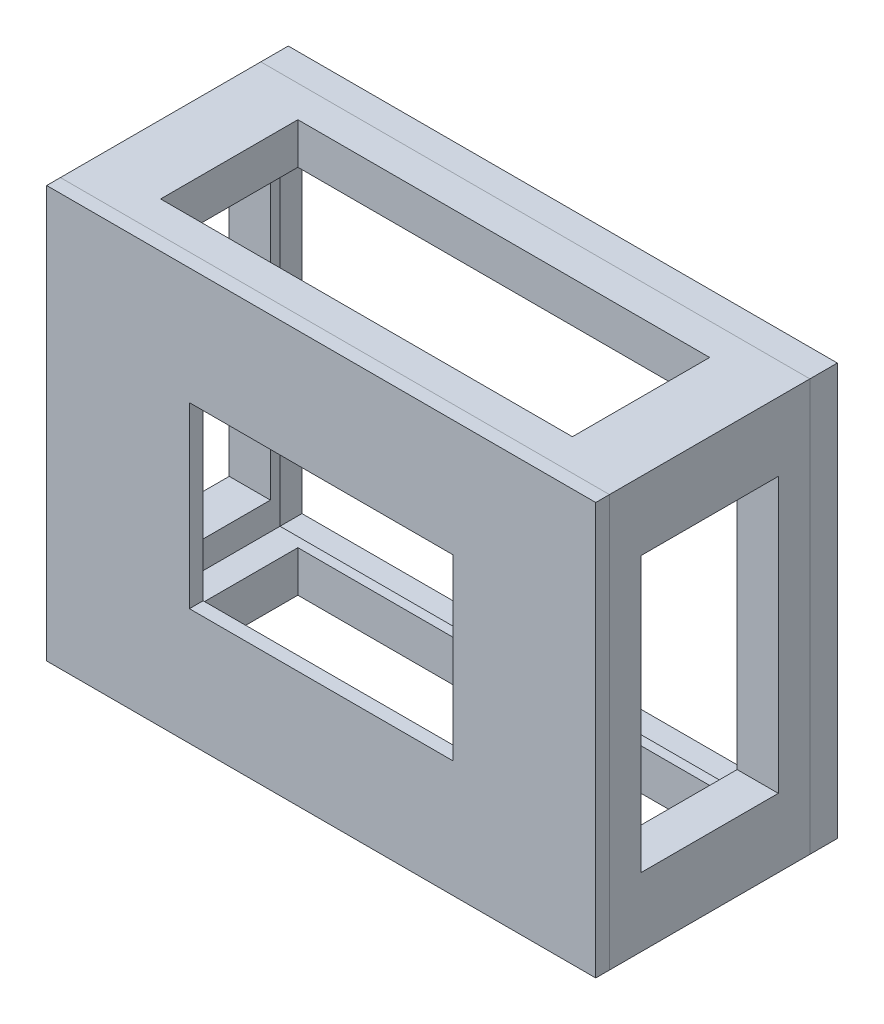
SolidWorks part; units mm, degrees
ref_plane "Front Plane" through (0, 0, 0) normal (1, 0, 0) x (0, 1, 0)
ref_plane "Top Plane" through (0, 0, 0) normal (0, 0, 1) x (0, 1, 0)
ref_plane "Right Plane" through (0, 0, 0) normal (0, 1, 0) x (-1, 0, 0)
sketch "Sketch1" plane through (0, 0, 0) normal (0, 0, 1) x (0, 1, 0)
  line L5 (-6.5, -9.6) -> (6.5, -9.6)
  line L6 (-6.5, -9.6) -> (-6.5, 9.6)
  line L7 (-6.5, 9.6) -> (6.5, 9.6)
  line L8 (6.5, -9.6) -> (6.5, 9.6)
  line L9 (-6.5, -9.6) -> (6.5, 9.6) construction
  line L10 (-6.5, 9.6) -> (6.5, -9.6) construction
  line L11 (-15, -20) -> (15, -20)
  line L12 (-15, -20) -> (-15, 20)
  line L13 (-15, 20) -> (15, 20)
  line L14 (15, -20) -> (15, 20)
  line L15 (-15, -20) -> (15, 20) construction
  line L16 (-15, 20) -> (15, -20) construction
  point P0 (0, 0)
  point P7 (0, 0)
  dimension "D1" = 13
  dimension "D2" = 19.2
  dimension "D3" = 30
  dimension "D4" = 40
extrude "Boss-Extrude1" add sketch "Sketch1" along normal blind 1
sketch "Sketch2" plane through (0, 0, 0) normal (0, 0, -1) x (1, 0, 0)
  line L0 (-17, -12) -> (17, -12)
  line L1 (17, -12) -> (17, 12)
  line L2 (17, 12) -> (-17, 12)
  line L3 (-17, 12) -> (-17, -12)
  line L4 (-20, -15) -> (20, -15)
  line L5 (20, -15) -> (20, 15)
  line L6 (20, 15) -> (-20, 15)
  line L7 (-20, 15) -> (-20, -15)
  line L8 (-20, -15) -> (20, -15)
  line L9 (20, -15) -> (20, 15)
  line L10 (20, 15) -> (-20, 15)
  line L11 (-20, 15) -> (-20, -15)
  dimension "D1" = 0
  dimension "D2" = 3
extrude "Boss-Extrude2" add sketch "Sketch2" along normal blind 13 separate body
sketch "Sketch3" plane through (0, 0, -13) normal (0, 0, -1) x (1, 0, 0)
  line L0 (-19, 14) -> (-19, -14)
  line L1 (-19, -14) -> (19, -14)
  line L2 (19, -14) -> (19, 14)
  line L3 (19, 14) -> (-19, 14)
  line L4 (-20, 15) -> (-20, -15)
  line L5 (-20, -15) -> (20, -15)
  line L6 (20, -15) -> (20, 15)
  line L7 (20, 15) -> (-20, 15)
  line L8 (-20, 15) -> (-20, -15)
  line L9 (-20, -15) -> (20, -15)
  line L10 (20, -15) -> (20, 15)
  line L11 (20, 15) -> (-20, 15)
  dimension "D1" = 0
  dimension "D2" = 1
extrude "Boss-Extrude3" add sketch "Sketch3" along normal blind 1.6
sketch "Sketch4" plane through (0, 0, -14.6) normal (0, 0, -1) x (1, 0, 0)
  line L0 (-19, 14) -> (-19, -14) construction
  line L1 (-19, -14) -> (19, -14) construction
  line L2 (19, -14) -> (19, 14) construction
  line L3 (19, -14) -> (19, 14)
  line L4 (20, 15) -> (-20, 15)
  line L5 (-20, 15) -> (-20, -15)
  line L6 (-20, -15) -> (20, -15)
  line L7 (20, -15) -> (20, 15)
  line L8 (20, 15) -> (-20, 15)
  line L9 (-20, 15) -> (-20, -15)
  line L10 (-20, -15) -> (20, -15)
  line L11 (20, -15) -> (20, 15)
  line L12 (-19, -14) -> (-1, -14)
  line L13 (-19, 14) -> (-19, -14)
  line L14 (19, 14) -> (-19, 14) construction
  line L15 (19, 14) -> (1, 14)
  line L16 (0, 15) -> (0, -15) construction
  line L17 (1, -14) -> (1, -13)
  line L20 (-1, -13) -> (-1, -14)
  line L21 (1, -14) -> (19, -14)
  line L22 (19, 0) -> (-19, 0) construction
  line L23 (-1, 13) -> (-1, 14)
  line L25 (1, 14) -> (1, 13)
  line L26 (-1, 14) -> (-19, 14)
  line L27 (-1, 13) -> (1, 13)
  line L28 (-1, -13) -> (1, -13)
  dimension "D2" = 1
  dimension "D3" = 1
  dimension "D4" = 1
  dimension "D5" = 1
  dimension "D1" = 0
extrude "Boss-Extrude4" add sketch "Sketch4" along normal blind 2 separate body
chamfer "Chamfer1" distance 0.5 angle 45 2 edges at (0, 13, -14.6) (0, 13, -16.6)
chamfer "Chamfer2" distance 0.5 angle 45 2 edges at (0, -13, -14.6) (0, -13, -16.6)
sketch "Sketch5" plane through (0, -15, 0) normal (0, -1, 0) x (1, 0, 0)
  line L0 (0, 0) -> (0, -14.6) construction
  line L1 (-20, 0) -> (20, 0) construction
  line L2 (20, -14.6) -> (-20, -14.6) construction
  line L3 (-20, -7.3) -> (20, -7.3) construction
  line L4 (-20, -14.6) -> (-20, 0) construction
  line L5 (20, -14.6) -> (20, 0) construction
  line L7 (-15, -12.3) -> (15, -12.3)
  line L8 (-15, -12.3) -> (-15, -2.3)
  line L9 (-15, -2.3) -> (15, -2.3)
  line L10 (15, -12.3) -> (15, -2.3)
  line L11 (-15, -12.3) -> (15, -2.3) construction
  line L12 (-15, -2.3) -> (15, -12.3) construction
  point P12 (0, -7.3)
  dimension "D1" = 10
  dimension "D2" = 30
extrude "Cut-Extrude1" cut sketch "Sketch5" against normal blind 70
sketch "Sketch6" plane through (20, 0, 0) normal (1, 0, 0) x (0, 1, 0)
  line L0 (0, 0) -> (0, -7.3) construction
  line L1 (0, -7.3) -> (-15, -7.3) construction
  line L2 (-15, -14.6) -> (-15, 0) construction
  line L4 (-10, -12.3) -> (10, -12.3)
  line L5 (-10, -12.3) -> (-10, -2.3)
  line L6 (-10, -2.3) -> (10, -2.3)
  line L7 (10, -12.3) -> (10, -2.3)
  line L8 (-10, -12.3) -> (10, -2.3) construction
  line L9 (-10, -2.3) -> (10, -12.3) construction
  dimension "D1" = 10
  dimension "D2" = 20
extrude "Cut-Extrude2" cut sketch "Sketch6" against normal blind 70
